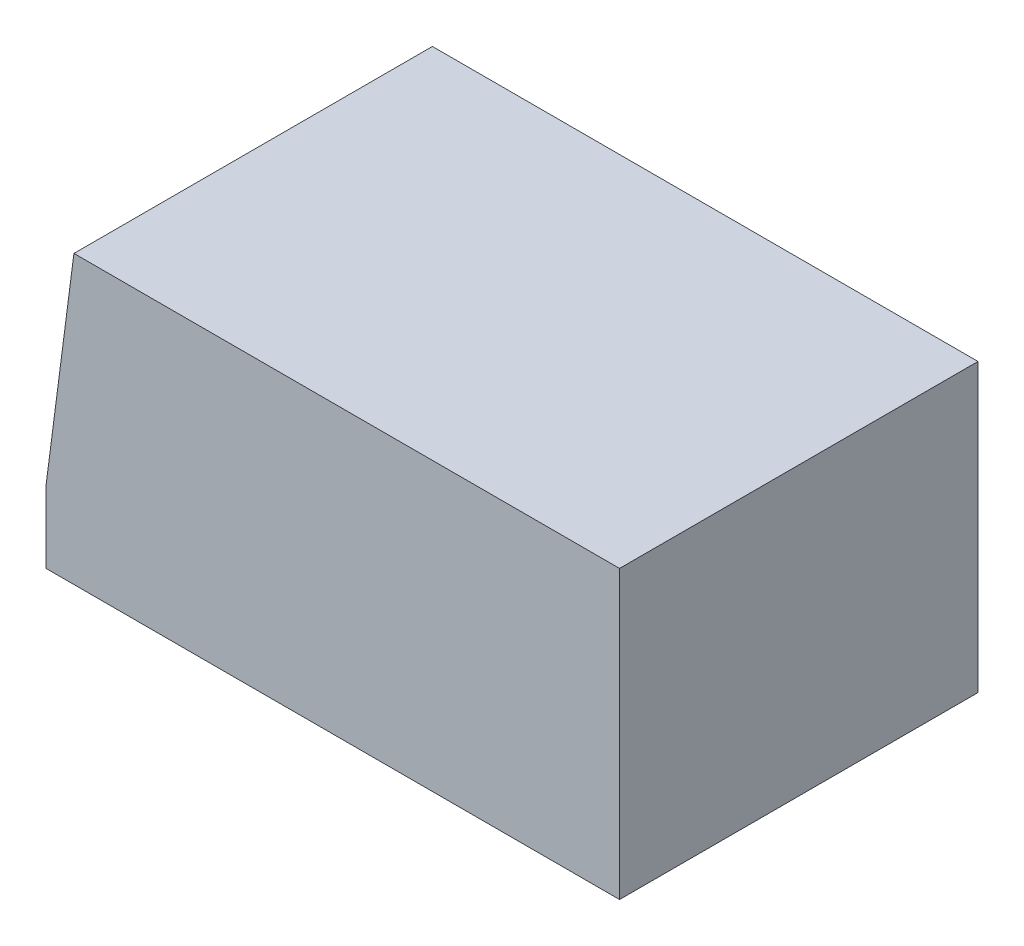
SolidWorks part; units mm, degrees
ref_plane "Plan de face" through (0, 0, 0) normal (0, 0, 1) x (1, 0, 0)
ref_plane "Plan de dessus" through (0, 0, 0) normal (0, 1, 0) x (1, 0, 0)
ref_plane "Plan de droite" through (0, 0, 0) normal (1, 0, 0) x (0, 0, -1)
sketch "Esquisse1" plane through (0, 0, 0) normal (0, 1, 0) x (1, 0, 0)
  line L1 (-40, -25) -> (40, -25)
  line L2 (-40, -25) -> (-40, 25)
  line L3 (-40, 25) -> (40, 25)
  line L4 (40, -25) -> (40, 25)
  line L5 (-40, -25) -> (40, 25) construction
  line L6 (-40, 25) -> (40, -25) construction
  point P0 (0, 0)
  dimension "D1" = 50
  dimension "D2" = 80
extrude "Boss.-Extru.1" add sketch "Esquisse1" along normal blind 40
chamfer "Chanfrein1" distance 30 angle 7.4 1 edges at (-40, 40, 0)
sketch "Esquisse2" plane through (-40.6137, 5.2748, 0) normal (-0.9917, 0.1288, 0) x (0, 0, 1)
  line L0 (25, 18.821) -> (-25, 18.821) construction
  line L3 (25, 35.0169) -> (25, 4.7649) construction
  line L4 (-25, 4.7649) -> (-25, 35.0169) construction
  circle A0 centre (0, 18.821) radius 12.5
  dimension "D1" = 25
extrude "Enlèv. mat.-Extru.1" cut sketch "Esquisse2" against normal blind 40
